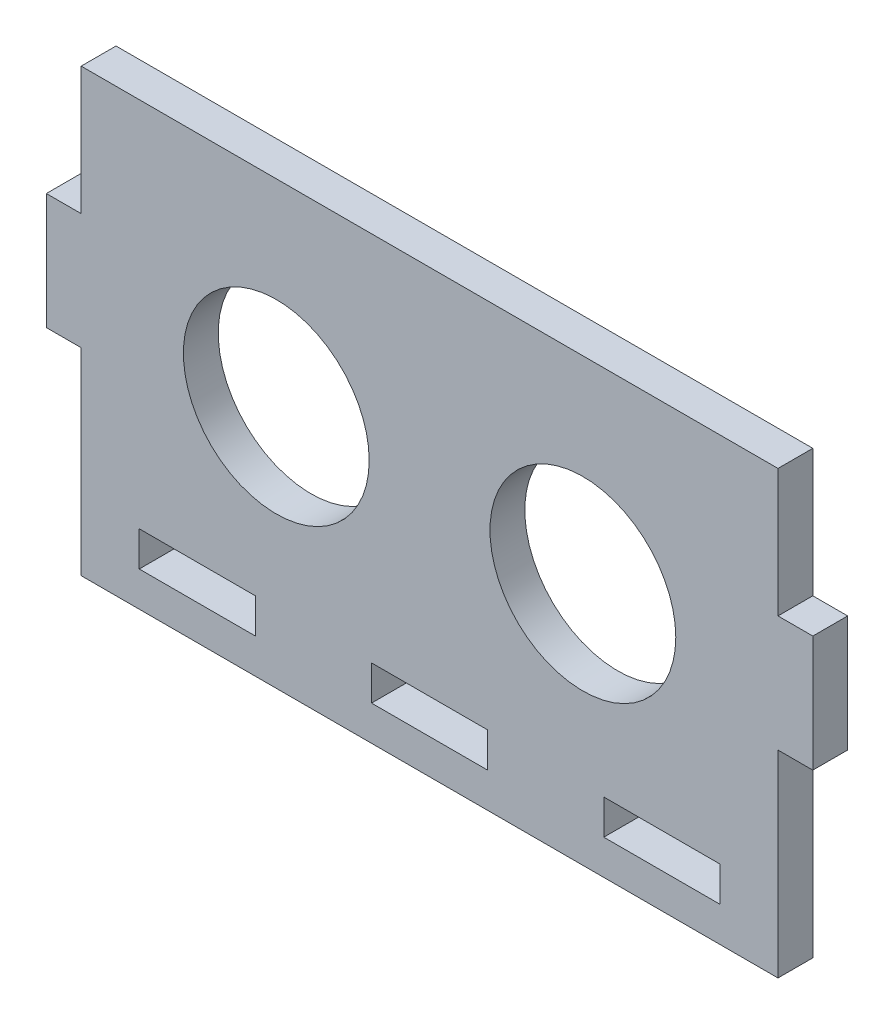
SolidWorks part; units mm, degrees
ref_plane "Front Plane" through (0, 0, 0) normal (0, 0, 1) x (1, 0, 0)
ref_plane "Top Plane" through (0, 0, 0) normal (0, 1, 0) x (1, 0, 0)
ref_plane "Right Plane" through (0, 0, 0) normal (1, 0, 0) x (0, 0, -1)
sketch "Sketch1" plane through (0, 0, 0) normal (0, 0, 1) x (1, 0, 0)
  line L1 (-32.8507, 15.0679) -> (27.1493, 15.0679)
  line L2 (-32.8507, 15.0679) -> (-32.8507, -22.9321)
  line L3 (-32.8507, -22.9321) -> (27.1493, -22.9321)
  line L4 (27.1493, 15.0679) -> (27.1493, -22.9321)
  line L5 (27.1493, 4.0679) -> (30.1493, 4.0679)
  line L6 (30.1493, 4.0679) -> (30.1493, -5.9321)
  line L7 (30.1493, -5.9321) -> (27.1493, -5.9321)
  line L8 (-7.8507, -16.9321) -> (2.1493, -16.9321)
  line L9 (22.1493, -16.9321) -> (12.1493, -16.9321)
  line L10 (22.1493, -16.9321) -> (22.1493, -19.9321)
  line L11 (22.1493, -19.9321) -> (12.1493, -19.9321)
  line L12 (12.1493, -16.9321) -> (12.1493, -19.9321)
  line L13 (2.1493, -16.9321) -> (2.1493, -19.9321)
  line L14 (2.1493, -19.9321) -> (-7.8507, -19.9321)
  line L15 (-35.8507, -5.9321) -> (-32.8507, -5.9321)
  line L16 (-35.8507, 4.0679) -> (-35.8507, -5.9321)
  line L17 (-32.8507, 4.0679) -> (-35.8507, 4.0679)
  line L18 (-7.8507, -16.9321) -> (-7.8507, -19.9321)
  line L19 (-17.8507, -16.9321) -> (-17.8507, -19.9321)
  line L20 (-27.8507, -19.9321) -> (-17.8507, -19.9321)
  line L21 (-27.8507, -16.9321) -> (-27.8507, -19.9321)
  line L22 (-27.8507, -16.9321) -> (-17.8507, -16.9321)
  circle A0 centre (10.3493, -1.9321) radius 8
  circle A1 centre (-16.0507, -1.9321) radius 8
  point P23 (-2.8507, -19.9321)
  point P28 (-2.8507, -16.9321)
  dimension "D15" = 16
  dimension "D16" = 17
  dimension "D17" = 16.8
  dimension "D18" = 16
  dimension "D19" = 26.4
  dimension "D20" = 17
  dimension "D1" = 60
  dimension "D2" = 38
  dimension "D3" = 11
  dimension "D4" = 3
  dimension "D5" = 10
  dimension "D6" = 17
  dimension "D7" = 10
  dimension "D8" = 3
  dimension "D9" = 3
  dimension "D10" = 5
  dimension "D11" = 10
  dimension "D12" = 3
  dimension "D13" = 3
  dimension "D14" = 5
extrude "Boss-Extrude1" add sketch "Sketch1" along normal blind 3 contours L4 L1 L2 L3 A1 A0 L18 L8 L13 L14 L12 L9 L10 L11 L21 L22 L19 L20 | L2 L17 L16 L15 | L7 L6 L5 L4
